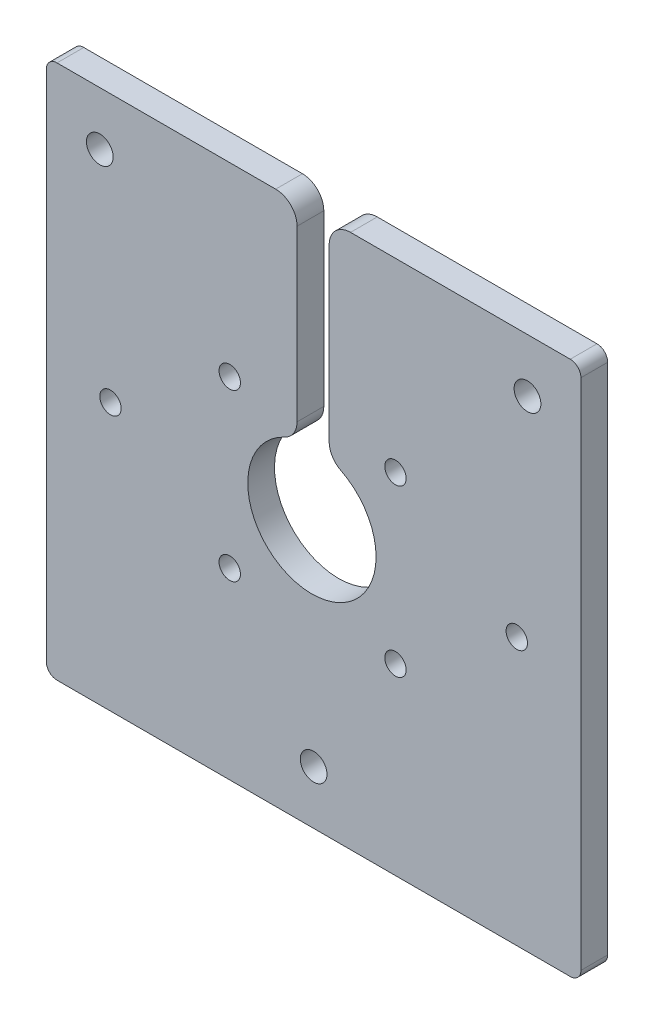
SolidWorks part; units mm, degrees
ref_plane "Front Plane" through (0, 0, 0) normal (0, 0, 1) x (1, 0, 0)
ref_plane "Top Plane" through (0, 0, 0) normal (0, 1, 0) x (1, 0, 0)
ref_plane "Right Plane" through (0, 0, 0) normal (1, 0, 0) x (0, 0, -1)
ref_plane "Plane1" through (0, 0, 701.6779) normal (0, 0, -1) x (-1, 0, 0)
sketch "Sketch1" plane through (0, 0, 701.6779) normal (0, 0, -1) x (-1, 0, 0)
  line L0 (-99.7198, 143.5257) -> (-99.7198, 111.8334)
  line L1 (-105.7198, 111.6169) -> (-105.7198, 143.5257)
  line L2 (-109.7198, 147.5257) -> (-150.8161, 147.5257)
  line L3 (-152.8161, 145.5257) -> (-152.8161, 49.5257)
  line L4 (-150.8161, 47.5257) -> (-54.8161, 47.5257)
  line L5 (-52.8161, 49.5257) -> (-52.8161, 145.5257)
  line L6 (-54.8161, 147.5257) -> (-95.7198, 147.5257)
  circle A0 centre (-87.1235, 81.8398) radius 2
  circle A1 centre (-118.1235, 81.8398) radius 2
  circle A2 centre (-87.1235, 112.8398) radius 2
  circle A3 centre (-118.1235, 112.8398) radius 2
  arc A4 (-95.7198, 147.5257) -> (-99.7198, 143.5257) centre (-95.7198, 143.5257) ccw
  arc A5 (-99.7198, 111.8334) -> (-97.4142, 108.21) centre (-95.7198, 111.8334) ccw
  arc A6 (-97.4142, 108.21) -> (-107.9142, 108.0476) centre (-102.4973, 97.3398) cw
  arc A7 (-107.9142, 108.0476) -> (-105.7198, 111.6169) centre (-109.7198, 111.6169) ccw
  arc A8 (-105.7198, 143.5257) -> (-109.7198, 147.5257) centre (-109.7198, 143.5257) ccw
  arc A9 (-150.8161, 147.5257) -> (-152.8161, 145.5257) centre (-150.8161, 145.5257) ccw
  arc A10 (-152.8161, 49.5257) -> (-150.8161, 47.5257) centre (-150.8161, 49.5257) ccw
  arc A11 (-54.8161, 47.5257) -> (-52.8161, 49.5257) centre (-54.8161, 49.5257) ccw
  arc A12 (-52.8161, 145.5257) -> (-54.8161, 147.5257) centre (-54.8161, 145.5257) ccw
  circle A13 centre (-102.8161, 57.5257) radius 2.5
  circle A14 centre (-62.8161, 137.5257) radius 2.5
  circle A15 centre (-142.8161, 137.5257) radius 2.5
  circle A16 centre (-64.8161, 97.5257) radius 2
  circle A17 centre (-140.8161, 97.5257) radius 2
  dimension "D3" = 10
  dimension "D4" = 10
  dimension "D5" = 10
  dimension "D6" = 50
  dimension "D7" = 50
  dimension "D8" = 37.0963
  dimension "D9" = 36.9037
  dimension "D14" = 12
  dimension "D15" = 4
  dimension "D16" = 49.8141
  dimension "D17" = 4
  dimension "D18" = 4
  dimension "D19" = 4
  dimension "D20" = 4
  dimension "D21" = 4
  dimension "D22" = 4
  dimension "D23" = 4
  dimension "D24" = 2
  dimension "D1" = 10
  dimension "D2" = 10
  dimension "D10" = 96
  dimension "D11" = 96
  dimension "D12" = 96
  dimension "D13" = 100
extrude "Boss-Extrude1" add sketch "Sketch1" against normal blind 5
